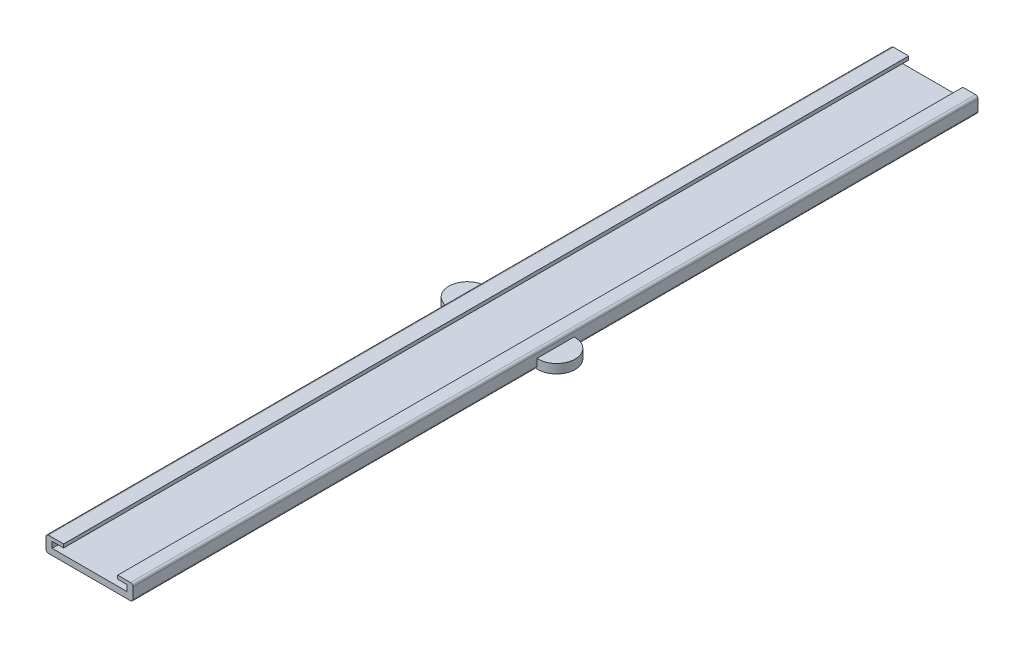
SolidWorks part; units mm, degrees
ref_plane "Front Plane" through (0, 0, 0) normal (0, 0, 1) x (1, 0, 0)
ref_plane "Top Plane" through (0, 0, 0) normal (0, 1, 0) x (1, 0, 0)
ref_plane "Right Plane" through (0, 0, 0) normal (1, 0, 0) x (0, 0, -1)
sketch "Sketch2" plane through (0, 0, 0) normal (0, 0, 1) x (1, 0, 0)
  line L0 (-8.5725, 0) -> (8.5725, 0)
  line L1 (9.0805, 0.508) -> (9.0805, 2.794)
  line L2 (-9.0805, 0.508) -> (-9.0805, 2.794)
  line L3 (8.5725, 3.302) -> (5.9055, 3.302)
  line L4 (-8.5725, 3.302) -> (-5.3975, 3.302)
  line L5 (-5.3975, 3.302) -> (-5.3975, 2.5654)
  line L6 (5.9055, 3.302) -> (5.9055, 2.5654)
  line L7 (-5.3975, 2.5654) -> (-7.8105, 2.5654)
  line L8 (5.9055, 2.5654) -> (7.8105, 2.5654)
  line L9 (-7.8105, 2.5654) -> (-7.8105, 1.2954)
  line L10 (-7.8105, 1.2954) -> (7.8105, 1.2954)
  line L11 (7.8105, 1.2954) -> (7.8105, 2.5654)
  arc A0 (-8.5725, 0) -> (-9.0805, 0.508) centre (-8.5725, 0.508) cw
  arc A1 (9.0805, 0.508) -> (8.5725, 0) centre (8.5725, 0.508) cw
  arc A2 (9.0805, 2.794) -> (8.5725, 3.302) centre (8.5725, 2.794) ccw
  arc A3 (-9.0805, 2.794) -> (-8.5725, 3.302) centre (-8.5725, 2.794) cw
  point P4 (0, 0)
  point P16 (-9.0805, 0)
  point P19 (9.0805, 0)
  point P22 (9.0805, 3.302)
  point P25 (-9.0805, 3.302)
  dimension "D11" = 0.508
  dimension "D1" = 18.161
  dimension "D2" = 3.302
  dimension "D3" = 3.302
  dimension "D4" = 3.175
  dimension "D5" = 3.683
  dimension "D6" = 0.7366
  dimension "D7" = 0.7366
  dimension "D8" = 2.413
  dimension "D9" = 1.905
  dimension "D10" = 1.27
extrude "Boss-Extrude1" add sketch "Sketch2" against normal blind 176.53
sketch "Sketch3" plane through (0, 0, 0) normal (0, 1, 0) x (1, 0, 0)
  line L0 (8.5725, 176.53) -> (8.5725, 0) construction
  line L1 (-1.8161, 0) -> (1.8161, 0) construction
  line L2 (8.5725, 176.53) -> (8.5725, 0) construction
  line L3 (8.5725, 88.265) -> (13.6525, 88.265) construction
  line L4 (8.5725, 84.455) -> (8.5725, 92.075)
  arc A0 (8.5725, 92.075) -> (8.5725, 84.455) centre (9.3124, 88.265) cw
  point P12 (8.5725, 88.265)
  dimension "D1" = 7.62
extrude "Boss-Extrude2" add sketch "Sketch3" along normal blind 1.905
mirror "Mirror1" about plane through (0, 0, 0) normal (1, 0, 0) of "Boss-Extrude2"
